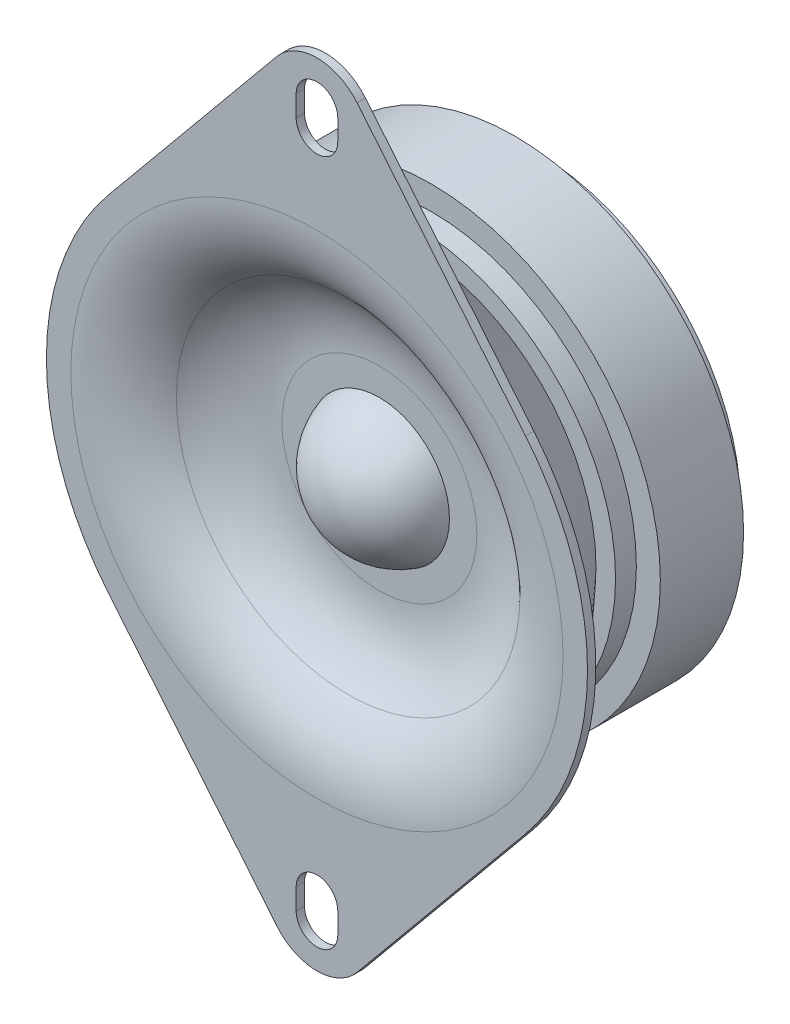
SolidWorks part; units mm, degrees
ref_plane "前视基准面" through (0, 0, 0) normal (0, 0, 1) x (1, 0, 0)
ref_plane "上视基准面" through (0, 0, 0) normal (0, 1, 0) x (1, 0, 0)
ref_plane "右视基准面" through (0, 0, 0) normal (1, 0, 0) x (0, 0, -1)
sketch "草图1" plane through (0, 0, 0) normal (0, 0, 1) x (1, 0, 0)
  circle A0 centre (0, 0) radius 26
  dimension "D1" = 52
ref_plane "基准面1" through (0, 0, -11) normal (0, 0, 1) x (1, 0, 0)
sketch "草图2" plane through (0, 0, -11) normal (0, 0, 1) x (1, 0, 0)
  circle A0 centre (0, 0) radius 16
  dimension "D1" = 32
loft "放样1" add profiles "草图1", "草图2"
shell "抽壳1" thickness 5
fillet "圆角1" radius 10 1 edges at (13.7882, 0, -6)
sketch "草图3" plane through (0, 0, 0) normal (0, 1, 0) x (1, 0, 0)
  line L0 (0, -7.1416) -> (0, 23.159) construction
  line L1 (0, 6) -> (6.7319, 6)
  line L2 (-9.3645, 6) -> (9.3645, 6) construction
  line L3 (0, 6) -> (0, 0.9186)
  arc A0 (0, 0.9186) -> (6.7319, 6) centre (0, 7.9186) ccw
  dimension "D1" = 7
revolve "旋转1" add sketch "草图3" angle 360 about L0
sketch "草图4" plane through (0, 0, -11) normal (0, 0, -1) x (-1, 0, 0)
  circle A0 centre (0, 0) radius 22
  dimension "D1" = 44
extrude "拉伸1" add sketch "草图4" along normal blind 8
ref_plane "基准面2" through (0, 0, -21) normal (0, 0, -1) x (-1, 0, 0)
sketch "草图5" plane through (0, 0, -21) normal (0, 0, -1) x (-1, 0, 0)
  circle A0 centre (0, 0) radius 19.6964
extrude "拉伸2" add sketch "草图5" against normal blind 12
fillet "圆角2" radius 10 1 edges at (19.2427, 0, 0)
sketch "草图6" plane through (0, 0, 0) normal (0, 0, 1) x (1, 0, 0)
  line L0 (0, 71.1113) -> (0, -64.7873) construction
  line L1 (-3.8569, 36.1818) -> (-20.0561, 16.5455)
  line L2 (3.8569, 36.1818) -> (20.0561, 16.5455)
  line L3 (-60.3044, 0) -> (49.5946, 0) construction
  line L4 (-3.8569, -36.1818) -> (-20.0561, -16.5455)
  line L5 (3.8569, -36.1818) -> (20.0561, -16.5455)
  line L6 (-2, 34) -> (-2, 32)
  line L7 (2, 34) -> (2, 32)
  line L8 (-2, 34) -> (2, 34) construction
  line L9 (-2, 32) -> (2, 32) construction
  line L10 (-2, -32) -> (2, -32) construction
  line L11 (-2, -34) -> (2, -34) construction
  line L12 (2, -34) -> (2, -32)
  line L13 (-2, -34) -> (-2, -32)
  line L14 (-2, 33) -> (2, 33) construction
  line L15 (-2, -33) -> (2, -33) construction
  circle A0 centre (0, 0) radius 26 construction
  arc A1 (-20.0561, 16.5455) -> (-20.0561, -16.5455) centre (0, 0) ccw
  arc A2 (3.8569, 36.1818) -> (-3.8569, 36.1818) centre (0, 33) ccw
  arc A3 (3.8569, -36.1818) -> (-3.8569, -36.1818) centre (0, -33) cw
  arc A4 (-2, -32) -> (2, -32) centre (0, -32) cw
  arc A5 (20.0561, -16.5455) -> (20.0561, 16.5455) centre (0, 0) ccw
  arc A6 (2, 34) -> (-2, 34) centre (0, 34) ccw
  arc A7 (-2, 32) -> (2, 32) centre (0, 32) ccw
  arc A8 (2, -34) -> (-2, -34) centre (0, -34) cw
  circle A13 centre (0, 0) radius 23.6473 construction
  circle A14 centre (0, 0) radius 23.6473
  point P11 (0, 40.8571)
  dimension "D1" = 5
  dimension "D2" = 76
  dimension "D3" = 2
  dimension "D5" = 2
  dimension "D6" = 66
extrude "拉伸3" add sketch "草图6" against normal blind 0.8
